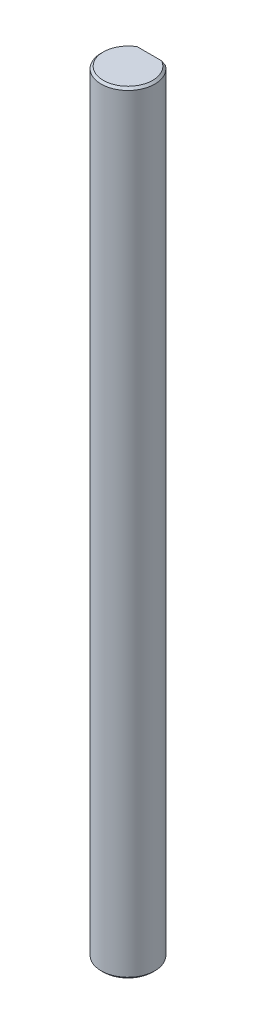
SolidWorks part; units mm, degrees
ref_plane "Alzado" through (0, 0, 0) normal (0, 0, 1) x (1, 0, 0)
ref_plane "Planta" through (0, 0, 0) normal (0, 1, 0) x (1, 0, 0)
ref_plane "Vista lateral" through (0, 0, 0) normal (1, 0, 0) x (0, 0, -1)
sketch "Croquis1" plane through (0, 0, 0) normal (0, 1, 0) x (1, 0, 0)
  circle A0 centre (0, 0) radius 2.5
  dimension "D1" = 5
extrude "Saliente-Extruir1" add sketch "Croquis1" along normal blind 72 contours A0
sketch "Croquis2" plane through (0, 72, 0) normal (0, 1, 0) x (1, 0, 0)
  line L0 (-1.5, 2) -> (1.5, 2)
  line L1 (0, -2.5) -> (0, 2) construction
  circle A0 centre (0, 0) radius 2.5 construction
  arc A1 (1.5, 2) -> (-1.5, 2) centre (0, 0) ccw
  dimension "D1" = 4.5
extrude "Cortar-Extruir1" cut sketch "Croquis2" against normal blind 10
chamfer "Chaflán1" distance 0.2 angle 45 2 edges at (0, 0, 2.5) (0, 72, 2.5)
